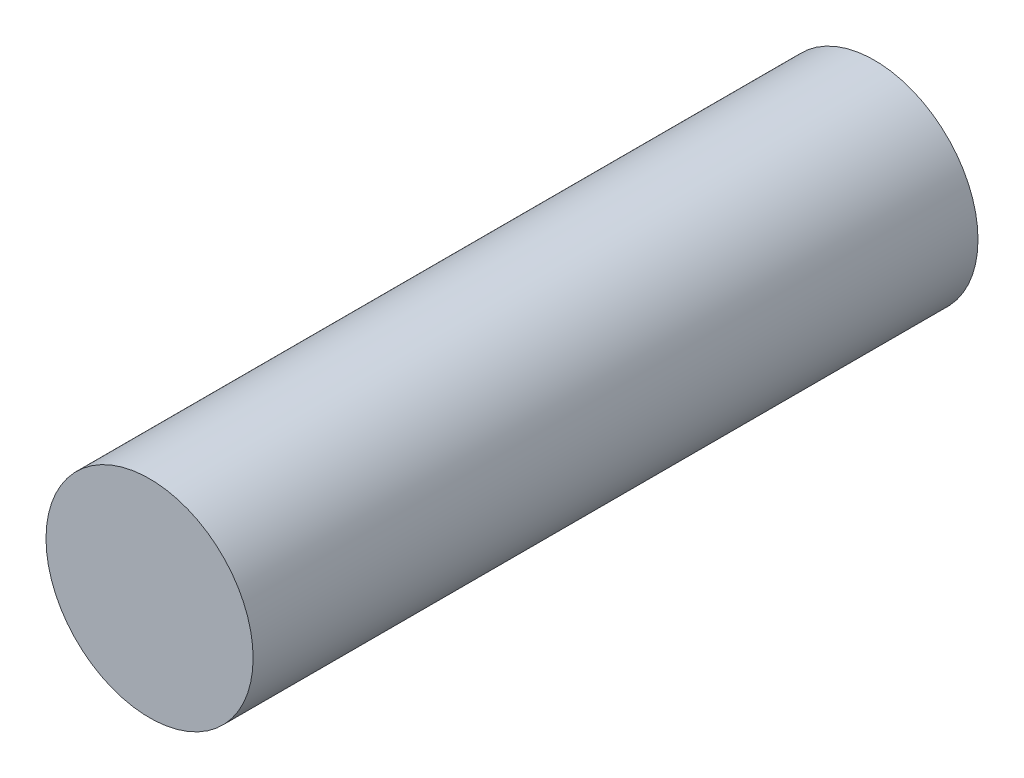
SolidWorks part; units mm, degrees
material "Brass"
ref_plane "Front Plane" through (0, 0, 0) normal (0, 0, 1) x (1, 0, 0)
ref_plane "Top Plane" through (0, 0, 0) normal (0, 1, 0) x (1, 0, 0)
ref_plane "Right Plane" through (0, 0, 0) normal (1, 0, 0) x (0, 0, -1)
sketch "Sketch1" plane through (0, 0, 0) normal (0, 0, 1) x (1, 0, 0)
  circle A0 centre (0, 0) radius 3.175
  dimension "D1" = 6.35
extrude "Boss-Extrude1" add sketch "Sketch1" along normal mid plane 22.225 contours A0
